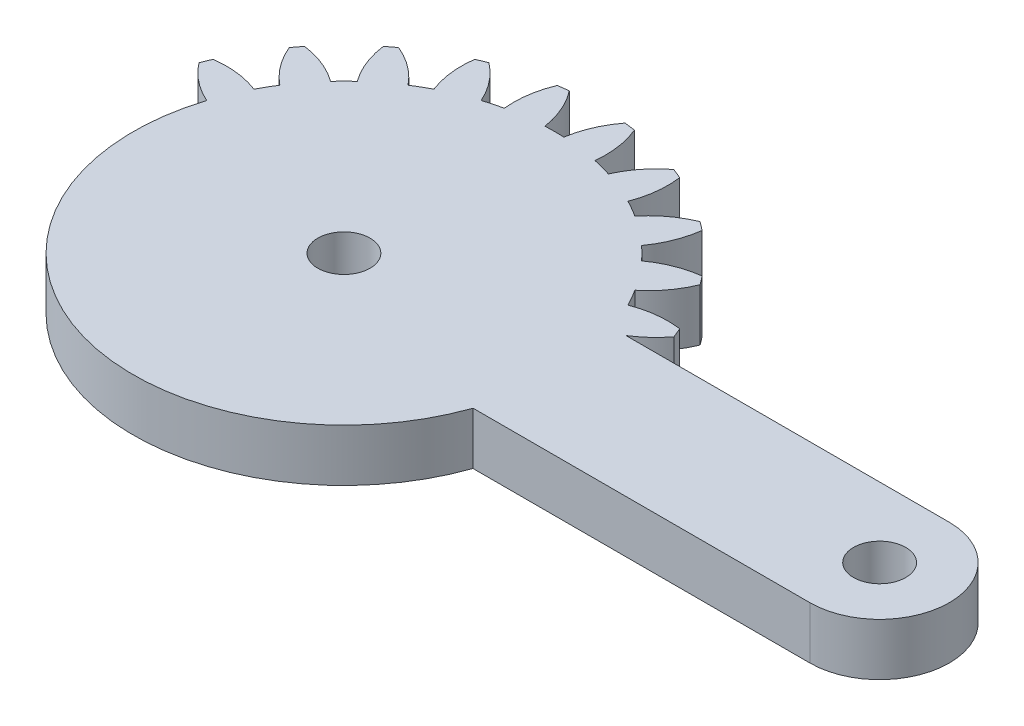
SolidWorks part; units mm, degrees
ref_plane "Front Plane" through (0, 0, 0) normal (0, 0, 1) x (1, 0, 0)
ref_plane "Top Plane" through (0, 0, 0) normal (0, 1, 0) x (1, 0, 0)
ref_plane "Right Plane" through (0, 0, 0) normal (1, 0, 0) x (0, 0, -1)
sketch "Sketch1" plane through (0, 0, 0) normal (0, 1, 0) x (1, 0, 0)
  line L0 (20.6437, 4) -> (2.0816, 4)
  line L1 (2.0816, -4) -> (20.6437, -4)
  arc A0 (2.0816, 4) -> (3.5217, 5.3071) centre (-0.7683, 8.5867) ccw
  arc A1 (3.5217, 5.3071) -> (3.2829, 5.8838) centre (-10.1063, 0) ccw
  arc A2 (3.2829, 5.8838) -> (0.6271, 5.5703) centre (2.5684, 0.5313) ccw
  arc A3 (0.6271, 5.5703) -> (0.0844, 6.5103) centre (-10.1063, 0) ccw
  arc A4 (0.0844, 6.5103) -> (1.6838, 8.6535) centre (-3.3089, 10.711) ccw
  arc A5 (1.6838, 8.6535) -> (1.3038, 9.1487) centre (-10.1063, 0) ccw
  arc A6 (1.3038, 9.1487) -> (-1.1803, 8.1585) centre (1.999, 3.7936) ccw
  arc A7 (-1.1803, 8.1585) -> (-1.9479, 8.926) centre (-10.1063, 0) ccw
  arc A8 (-1.9479, 8.926) -> (-0.9576, 11.4102) centre (-6.3127, 12.1053) ccw
  arc A9 (-0.9576, 11.4102) -> (-1.4528, 11.7901) centre (-10.1063, 0) ccw
  arc A10 (-1.4528, 11.7901) -> (-3.596, 10.1907) centre (0.6046, 6.7975) ccw
  arc A11 (-3.596, 10.1907) -> (-4.5361, 10.7334) centre (-10.1063, 0) ccw
  arc A12 (-4.5361, 10.7334) -> (-4.2225, 13.3892) centre (-9.5751, 12.6747) ccw
  arc A13 (-4.2225, 13.3892) -> (-4.7992, 13.6281) centre (-10.1063, 0) ccw
  arc A14 (-4.7992, 13.6281) -> (-6.4554, 11.5285) centre (-1.5196, 9.3381) ccw
  arc A15 (-6.4554, 11.5285) -> (-7.5039, 11.8094) centre (-10.1063, 0) ccw
  arc A16 (-7.5039, 11.8094) -> (-7.8884, 14.4558) centre (-12.8736, 12.3803) ccw
  arc A17 (-7.8884, 14.4558) -> (-8.5072, 14.5373) centre (-10.1063, 0) ccw
  arc A18 (-8.5072, 14.5373) -> (-9.5636, 12.0806) centre (-4.2291, 11.2423) ccw
  arc A19 (-9.5636, 12.0806) -> (-10.6491, 12.0806) centre (-10.1063, 0) ccw
  arc A20 (-10.6491, 12.0806) -> (-11.7054, 14.5373) centre (-15.9836, 11.2423) ccw
  arc A21 (-11.7054, 14.5373) -> (-12.3243, 14.4558) centre (-10.1063, 0) ccw
  arc A22 (-12.3243, 14.4558) -> (-12.7088, 11.8094) centre (-7.3391, 12.3803) ccw
  arc A23 (-12.7088, 11.8094) -> (-13.7573, 11.5285) centre (-10.1063, 0) ccw
  arc A24 (-13.7573, 11.5285) -> (-15.4135, 13.6281) centre (-18.6931, 9.3381) ccw
  arc A25 (-15.4135, 13.6281) -> (-15.9901, 13.3892) centre (-10.1063, 0) ccw
  arc A26 (-15.9901, 13.3892) -> (-15.6766, 10.7334) centre (-10.6376, 12.6747) ccw
  arc A27 (-15.6766, 10.7334) -> (-16.6166, 10.1907) centre (-10.1063, 0) ccw
  arc A28 (-16.6166, 10.1907) -> (-18.7599, 11.7901) centre (-20.8173, 6.7975) ccw
  arc A29 (-18.7599, 11.7901) -> (-19.255, 11.4102) centre (-10.1063, 0) ccw
  arc A30 (-19.255, 11.4102) -> (-18.2648, 8.926) centre (-13.9, 12.1053) ccw
  arc A31 (-18.2648, 8.926) -> (-19.0324, 8.1585) centre (-10.1063, 0) ccw
  arc A32 (-19.0324, 8.1585) -> (-21.5165, 9.1487) centre (-22.2117, 3.7936) ccw
  arc A33 (-21.5165, 9.1487) -> (-21.8965, 8.6535) centre (-10.1063, 0) ccw
  arc A34 (-21.8965, 8.6535) -> (-20.2971, 6.5103) centre (-16.9038, 10.711) ccw
  arc A35 (-20.2971, 6.5103) -> (-20.8398, 5.5703) centre (-10.1063, 0) ccw
  arc A36 (-20.8398, 5.5703) -> (-23.4956, 5.8838) centre (-22.7811, 0.5313) ccw
  arc A37 (-23.4956, 5.8838) -> (-23.7344, 5.3071) centre (-10.1063, 0) ccw
  arc A38 (-23.7344, 5.3071) -> (-21.6348, 3.6509) centre (-19.4444, 8.5867) ccw
  arc A39 (-21.6348, 3.6509) -> (-21.9157, 2.6025) centre (-10.1063, 0) ccw
  arc A40 (-21.9157, 2.6025) -> (-24.5622, 2.2179) centre (-22.4867, -2.7673) ccw
  arc A41 (-24.5622, 2.2179) -> (-24.6437, 1.5991) centre (-10.1063, 0) ccw
  arc A42 (-24.6437, 1.5991) -> (-22.1869, 0.5427) centre (-21.3486, 5.8773) ccw
  arc A43 (-22.1869, 0.5427) -> (-22.1869, -0.5427) centre (-10.1063, 0) ccw
  arc A44 (-22.1869, -0.5427) -> (-24.6437, -1.5991) centre (-21.3486, -5.8773) ccw
  arc A45 (-24.6437, -1.5991) -> (-24.5622, -2.2179) centre (-10.1063, 0) ccw
  arc A46 (-24.5622, -2.2179) -> (-21.9157, -2.6025) centre (-22.4867, 2.7673) ccw
  arc A47 (-21.9157, -2.6025) -> (-21.6348, -3.6509) centre (-10.1063, 0) ccw
  arc A48 (-21.6348, -3.6509) -> (-23.7344, -5.3071) centre (-19.4444, -8.5867) ccw
  arc A49 (-23.7344, -5.3071) -> (-23.4956, -5.8838) centre (-10.1063, 0) ccw
  arc A50 (-23.4956, -5.8838) -> (-20.8398, -5.5703) centre (-22.7811, -0.5313) ccw
  arc A51 (-20.8398, -5.5703) -> (-20.2971, -6.5103) centre (-10.1063, 0) ccw
  arc A52 (-20.2971, -6.5103) -> (-21.8965, -8.6535) centre (-16.9038, -10.711) ccw
  arc A53 (-21.8965, -8.6535) -> (-21.5165, -9.1487) centre (-10.1063, 0) ccw
  arc A54 (-21.5165, -9.1487) -> (-19.0324, -8.1585) centre (-22.2117, -3.7936) ccw
  arc A55 (-19.0324, -8.1585) -> (-18.2648, -8.926) centre (-10.1063, 0) ccw
  arc A56 (-18.2648, -8.926) -> (-19.255, -11.4102) centre (-13.9, -12.1053) ccw
  arc A57 (-19.255, -11.4102) -> (-18.7599, -11.7901) centre (-10.1063, 0) ccw
  arc A58 (-18.7599, -11.7901) -> (-16.6166, -10.1907) centre (-20.8173, -6.7975) ccw
  arc A59 (-16.6166, -10.1907) -> (-15.6766, -10.7334) centre (-10.1063, 0) ccw
  arc A60 (-15.6766, -10.7334) -> (-15.9901, -13.3892) centre (-10.6376, -12.6747) ccw
  arc A61 (-15.9901, -13.3892) -> (-15.4135, -13.6281) centre (-10.1063, 0) ccw
  arc A62 (-15.4135, -13.6281) -> (-13.7573, -11.5285) centre (-18.6931, -9.3381) ccw
  arc A63 (-13.7573, -11.5285) -> (-12.7088, -11.8094) centre (-10.1063, 0) ccw
  arc A64 (-12.7088, -11.8094) -> (-12.3243, -14.4558) centre (-7.3391, -12.3803) ccw
  arc A65 (-12.3243, -14.4558) -> (-11.7054, -14.5373) centre (-10.1063, 0) ccw
  arc A66 (-11.7054, -14.5373) -> (-10.6491, -12.0806) centre (-15.9836, -11.2423) ccw
  arc A67 (-10.6491, -12.0806) -> (-9.5636, -12.0806) centre (-10.1063, 0) ccw
  arc A68 (-9.5636, -12.0806) -> (-8.5072, -14.5373) centre (-4.2291, -11.2423) ccw
  arc A69 (-8.5072, -14.5373) -> (-7.8884, -14.4558) centre (-10.1063, 0) ccw
  arc A70 (-7.8884, -14.4558) -> (-7.5039, -11.8094) centre (-12.8736, -12.3803) ccw
  arc A71 (-7.5039, -11.8094) -> (-6.4554, -11.5285) centre (-10.1063, 0) ccw
  arc A72 (-6.4554, -11.5285) -> (-4.7992, -13.6281) centre (-1.5196, -9.3381) ccw
  arc A73 (-4.7992, -13.6281) -> (-4.2225, -13.3892) centre (-10.1063, 0) ccw
  arc A74 (-4.2225, -13.3892) -> (-4.5361, -10.7334) centre (-9.5751, -12.6747) ccw
  arc A75 (-4.5361, -10.7334) -> (-3.596, -10.1907) centre (-10.1063, 0) ccw
  arc A76 (-3.596, -10.1907) -> (-1.4528, -11.7901) centre (0.6046, -6.7975) ccw
  arc A77 (-1.4528, -11.7901) -> (-0.9576, -11.4102) centre (-10.1063, 0) ccw
  arc A78 (-0.9576, -11.4102) -> (-1.9479, -8.926) centre (-6.3127, -12.1053) ccw
  arc A79 (-1.9479, -8.926) -> (-1.1803, -8.1585) centre (-10.1063, 0) ccw
  arc A80 (-1.1803, -8.1585) -> (1.3038, -9.1487) centre (1.999, -3.7936) ccw
  arc A81 (1.3038, -9.1487) -> (1.6838, -8.6535) centre (-10.1063, 0) ccw
  arc A82 (1.6838, -8.6535) -> (0.0844, -6.5103) centre (-3.3089, -10.711) ccw
  arc A83 (0.0844, -6.5103) -> (0.6271, -5.5703) centre (-10.1063, 0) ccw
  arc A84 (0.6271, -5.5703) -> (3.2829, -5.8838) centre (2.5684, -0.5313) ccw
  arc A85 (3.2829, -5.8838) -> (3.5217, -5.3071) centre (-10.1063, 0) ccw
  arc A86 (3.5217, -5.3071) -> (2.0816, -4) centre (-0.7683, -8.5867) ccw
  arc A87 (20.6437, -4) -> (20.6437, 4) centre (20.6437, 0) ccw
  circle A88 centre (-10.1063, 0) radius 1.5
  circle A89 centre (20.6437, 0) radius 1.5
  dimension "D1" = 3
  dimension "D2" = 3
extrude "Boss-Extrude1" add sketch "Sketch1" along normal blind 3
sketch "Sketch2" plane through (0, 3, 0) normal (0, 1, 0) x (1, 0, 0)
  line L0 (2.0816, -4) -> (1.3057, -4)
  line L2 (20.6437, 4) -> (2.0816, 4)
  line L3 (2.0816, -4) -> (20.6437, -4)
  line L4 (20.6437, 4) -> (2.0816, 4)
  line L5 (2.0816, -4) -> (20.6437, -4)
  circle A0 centre (-10.1063, 0) radius 12.0927
  arc A88 (20.6437, -4) -> (20.6437, 4) centre (20.6437, 0) ccw
  arc A89 (2.0816, 4) -> (3.5217, 5.3071) centre (-0.7683, 8.5867) ccw
  arc A90 (3.5217, 5.3071) -> (3.2829, 5.8838) centre (-10.1063, 0) ccw
  arc A91 (3.2829, 5.8838) -> (0.6271, 5.5703) centre (2.5684, 0.5313) ccw
  arc A92 (0.6271, 5.5703) -> (0.0844, 6.5103) centre (-10.1063, 0) ccw
  arc A93 (0.0844, 6.5103) -> (1.6838, 8.6535) centre (-3.3089, 10.711) ccw
  arc A94 (1.6838, 8.6535) -> (1.3038, 9.1487) centre (-10.1063, 0) ccw
  arc A95 (1.3038, 9.1487) -> (-1.1803, 8.1585) centre (1.999, 3.7936) ccw
  arc A96 (-1.1803, 8.1585) -> (-1.9479, 8.926) centre (-10.1063, 0) ccw
  arc A97 (-1.9479, 8.926) -> (-0.9576, 11.4102) centre (-6.3127, 12.1053) ccw
  arc A98 (-0.9576, 11.4102) -> (-1.4528, 11.7901) centre (-10.1063, 0) ccw
  arc A99 (-1.4528, 11.7901) -> (-3.596, 10.1907) centre (0.6046, 6.7975) ccw
  arc A100 (-3.596, 10.1907) -> (-4.5361, 10.7334) centre (-10.1063, 0) ccw
  arc A101 (-4.5361, 10.7334) -> (-4.2225, 13.3892) centre (-9.5751, 12.6747) ccw
  arc A102 (-4.2225, 13.3892) -> (-4.7992, 13.6281) centre (-10.1063, 0) ccw
  arc A103 (-4.7992, 13.6281) -> (-6.4554, 11.5285) centre (-1.5196, 9.3381) ccw
  arc A104 (-6.4554, 11.5285) -> (-7.5039, 11.8094) centre (-10.1063, 0) ccw
  arc A105 (-7.5039, 11.8094) -> (-7.8884, 14.4558) centre (-12.8736, 12.3803) ccw
  arc A106 (-7.8884, 14.4558) -> (-8.5072, 14.5373) centre (-10.1063, 0) ccw
  arc A107 (-8.5072, 14.5373) -> (-9.5636, 12.0806) centre (-4.2291, 11.2423) ccw
  arc A108 (-9.5636, 12.0806) -> (-10.6491, 12.0806) centre (-10.1063, 0) ccw
  arc A109 (-10.6491, 12.0806) -> (-11.7054, 14.5373) centre (-15.9836, 11.2423) ccw
  arc A110 (-11.7054, 14.5373) -> (-12.3243, 14.4558) centre (-10.1063, 0) ccw
  arc A111 (-12.3243, 14.4558) -> (-12.7088, 11.8094) centre (-7.3391, 12.3803) ccw
  arc A112 (-12.7088, 11.8094) -> (-13.7573, 11.5285) centre (-10.1063, 0) ccw
  arc A113 (-13.7573, 11.5285) -> (-15.4135, 13.6281) centre (-18.6931, 9.3381) ccw
  arc A114 (-15.4135, 13.6281) -> (-15.9901, 13.3892) centre (-10.1063, 0) ccw
  arc A115 (-15.9901, 13.3892) -> (-15.6766, 10.7334) centre (-10.6376, 12.6747) ccw
  arc A116 (-15.6766, 10.7334) -> (-16.6166, 10.1907) centre (-10.1063, 0) ccw
  arc A117 (-16.6166, 10.1907) -> (-18.7599, 11.7901) centre (-20.8173, 6.7975) ccw
  arc A118 (-18.7599, 11.7901) -> (-19.255, 11.4102) centre (-10.1063, 0) ccw
  arc A119 (-19.255, 11.4102) -> (-18.2648, 8.926) centre (-13.9, 12.1053) ccw
  arc A120 (-18.2648, 8.926) -> (-19.0324, 8.1585) centre (-10.1063, 0) ccw
  arc A121 (-19.0324, 8.1585) -> (-21.5165, 9.1487) centre (-22.2117, 3.7936) ccw
  arc A122 (-21.5165, 9.1487) -> (-21.8965, 8.6535) centre (-10.1063, 0) ccw
  arc A123 (-21.8965, 8.6535) -> (-20.2971, 6.5103) centre (-16.9038, 10.711) ccw
  arc A124 (-20.2971, 6.5103) -> (-20.8398, 5.5703) centre (-10.1063, 0) ccw
  arc A125 (-20.8398, 5.5703) -> (-23.4956, 5.8838) centre (-22.7811, 0.5313) ccw
  arc A126 (-23.4956, 5.8838) -> (-23.7344, 5.3071) centre (-10.1063, 0) ccw
  arc A127 (-23.7344, 5.3071) -> (-21.6348, 3.6509) centre (-19.4444, 8.5867) ccw
  arc A128 (-21.6348, 3.6509) -> (-21.9157, 2.6025) centre (-10.1063, 0) ccw
  arc A129 (-21.9157, 2.6025) -> (-24.5622, 2.2179) centre (-22.4867, -2.7673) ccw
  arc A130 (-24.5622, 2.2179) -> (-24.6437, 1.5991) centre (-10.1063, 0) ccw
  arc A131 (-24.6437, 1.5991) -> (-22.1869, 0.5427) centre (-21.3486, 5.8773) ccw
  arc A132 (-22.1869, 0.5427) -> (-22.1869, -0.5427) centre (-10.1063, 0) ccw
  arc A133 (-22.1869, -0.5427) -> (-24.6437, -1.5991) centre (-21.3486, -5.8773) ccw
  arc A134 (-24.6437, -1.5991) -> (-24.5622, -2.2179) centre (-10.1063, 0) ccw
  arc A135 (-24.5622, -2.2179) -> (-21.9157, -2.6025) centre (-22.4867, 2.7673) ccw
  arc A136 (-21.9157, -2.6025) -> (-21.6348, -3.6509) centre (-10.1063, 0) ccw
  arc A137 (-21.6348, -3.6509) -> (-23.7344, -5.3071) centre (-19.4444, -8.5867) ccw
  arc A138 (-23.7344, -5.3071) -> (-23.4956, -5.8838) centre (-10.1063, 0) ccw
  arc A139 (-23.4956, -5.8838) -> (-20.8398, -5.5703) centre (-22.7811, -0.5313) ccw
  arc A140 (-20.8398, -5.5703) -> (-20.2971, -6.5103) centre (-10.1063, 0) ccw
  arc A141 (-20.2971, -6.5103) -> (-21.8965, -8.6535) centre (-16.9038, -10.711) ccw
  arc A142 (-21.8965, -8.6535) -> (-21.5165, -9.1487) centre (-10.1063, 0) ccw
  arc A143 (-21.5165, -9.1487) -> (-19.0324, -8.1585) centre (-22.2117, -3.7936) ccw
  arc A144 (-19.0324, -8.1585) -> (-18.2648, -8.926) centre (-10.1063, 0) ccw
  arc A145 (-18.2648, -8.926) -> (-19.255, -11.4102) centre (-13.9, -12.1053) ccw
  arc A146 (-19.255, -11.4102) -> (-18.7599, -11.7901) centre (-10.1063, 0) ccw
  arc A147 (-18.7599, -11.7901) -> (-16.6166, -10.1907) centre (-20.8173, -6.7975) ccw
  arc A148 (-16.6166, -10.1907) -> (-15.6766, -10.7334) centre (-10.1063, 0) ccw
  arc A149 (-15.6766, -10.7334) -> (-15.9901, -13.3892) centre (-10.6376, -12.6747) ccw
  arc A150 (-15.9901, -13.3892) -> (-15.4135, -13.6281) centre (-10.1063, 0) ccw
  arc A151 (-15.4135, -13.6281) -> (-13.7573, -11.5285) centre (-18.6931, -9.3381) ccw
  arc A152 (-13.7573, -11.5285) -> (-12.7088, -11.8094) centre (-10.1063, 0) ccw
  arc A153 (-12.7088, -11.8094) -> (-12.3243, -14.4558) centre (-7.3391, -12.3803) ccw
  arc A154 (-12.3243, -14.4558) -> (-11.7054, -14.5373) centre (-10.1063, 0) ccw
  arc A155 (-11.7054, -14.5373) -> (-10.6491, -12.0806) centre (-15.9836, -11.2423) ccw
  arc A156 (-10.6491, -12.0806) -> (-9.5636, -12.0806) centre (-10.1063, 0) ccw
  arc A157 (-9.5636, -12.0806) -> (-8.5072, -14.5373) centre (-4.2291, -11.2423) ccw
  arc A158 (-8.5072, -14.5373) -> (-7.8884, -14.4558) centre (-10.1063, 0) ccw
  arc A159 (-7.8884, -14.4558) -> (-7.5039, -11.8094) centre (-12.8736, -12.3803) ccw
  arc A160 (-7.5039, -11.8094) -> (-6.4554, -11.5285) centre (-10.1063, 0) ccw
  arc A161 (-6.4554, -11.5285) -> (-4.7992, -13.6281) centre (-1.5196, -9.3381) ccw
  arc A162 (-4.7992, -13.6281) -> (-4.2225, -13.3892) centre (-10.1063, 0) ccw
  arc A163 (-4.2225, -13.3892) -> (-4.5361, -10.7334) centre (-9.5751, -12.6747) ccw
  arc A164 (-4.5361, -10.7334) -> (-3.596, -10.1907) centre (-10.1063, 0) ccw
  arc A165 (-3.596, -10.1907) -> (-1.4528, -11.7901) centre (0.6046, -6.7975) ccw
  arc A166 (-1.4528, -11.7901) -> (-0.9576, -11.4102) centre (-10.1063, 0) ccw
  arc A167 (-0.9576, -11.4102) -> (-1.9479, -8.926) centre (-6.3127, -12.1053) ccw
  arc A168 (-1.9479, -8.926) -> (-1.1803, -8.1585) centre (-10.1063, 0) ccw
  arc A169 (-1.1803, -8.1585) -> (1.3038, -9.1487) centre (1.999, -3.7936) ccw
  arc A170 (1.3038, -9.1487) -> (1.6838, -8.6535) centre (-10.1063, 0) ccw
  arc A171 (1.6838, -8.6535) -> (0.0844, -6.5103) centre (-3.3089, -10.711) ccw
  arc A172 (0.0844, -6.5103) -> (0.6271, -5.5703) centre (-10.1063, 0) ccw
  arc A173 (0.6271, -5.5703) -> (3.2829, -5.8838) centre (2.5684, -0.5313) ccw
  arc A174 (3.2829, -5.8838) -> (3.5217, -5.3071) centre (-10.1063, 0) ccw
  arc A175 (3.5217, -5.3071) -> (2.0816, -4) centre (-0.7683, -8.5867) ccw
  arc A176 (20.6437, -4) -> (20.6437, 4) centre (20.6437, 0) ccw
  arc A177 (2.0816, 4) -> (3.5217, 5.3071) centre (-0.7683, 8.5867) ccw
  arc A178 (3.5217, 5.3071) -> (3.2829, 5.8838) centre (-10.1063, 0) ccw
  arc A179 (3.2829, 5.8838) -> (0.6271, 5.5703) centre (2.5684, 0.5313) ccw
  arc A180 (0.6271, 5.5703) -> (0.0844, 6.5103) centre (-10.1063, 0) ccw
  arc A181 (0.0844, 6.5103) -> (1.6838, 8.6535) centre (-3.3089, 10.711) ccw
  arc A182 (1.6838, 8.6535) -> (1.3038, 9.1487) centre (-10.1063, 0) ccw
  arc A183 (1.3038, 9.1487) -> (-1.1803, 8.1585) centre (1.999, 3.7936) ccw
  arc A184 (-1.1803, 8.1585) -> (-1.9479, 8.926) centre (-10.1063, 0) ccw
  arc A185 (-1.9479, 8.926) -> (-0.9576, 11.4102) centre (-6.3127, 12.1053) ccw
  arc A186 (-0.9576, 11.4102) -> (-1.4528, 11.7901) centre (-10.1063, 0) ccw
  arc A187 (-1.4528, 11.7901) -> (-3.596, 10.1907) centre (0.6046, 6.7975) ccw
  arc A188 (-3.596, 10.1907) -> (-4.5361, 10.7334) centre (-10.1063, 0) ccw
  arc A189 (-4.5361, 10.7334) -> (-4.2225, 13.3892) centre (-9.5751, 12.6747) ccw
  arc A190 (-4.2225, 13.3892) -> (-4.7992, 13.6281) centre (-10.1063, 0) ccw
  arc A191 (-4.7992, 13.6281) -> (-6.4554, 11.5285) centre (-1.5196, 9.3381) ccw
  arc A192 (-6.4554, 11.5285) -> (-7.5039, 11.8094) centre (-10.1063, 0) ccw
  arc A193 (-7.5039, 11.8094) -> (-7.8884, 14.4558) centre (-12.8736, 12.3803) ccw
  arc A194 (-7.8884, 14.4558) -> (-8.5072, 14.5373) centre (-10.1063, 0) ccw
  arc A195 (-8.5072, 14.5373) -> (-9.5636, 12.0806) centre (-4.2291, 11.2423) ccw
  arc A196 (-9.5636, 12.0806) -> (-10.6491, 12.0806) centre (-10.1063, 0) ccw
  arc A197 (-10.6491, 12.0806) -> (-11.7054, 14.5373) centre (-15.9836, 11.2423) ccw
  arc A198 (-11.7054, 14.5373) -> (-12.3243, 14.4558) centre (-10.1063, 0) ccw
  arc A199 (-12.3243, 14.4558) -> (-12.7088, 11.8094) centre (-7.3391, 12.3803) ccw
  arc A200 (-12.7088, 11.8094) -> (-13.7573, 11.5285) centre (-10.1063, 0) ccw
  arc A201 (-13.7573, 11.5285) -> (-15.4135, 13.6281) centre (-18.6931, 9.3381) ccw
  arc A202 (-15.4135, 13.6281) -> (-15.9901, 13.3892) centre (-10.1063, 0) ccw
  arc A203 (-15.9901, 13.3892) -> (-15.6766, 10.7334) centre (-10.6376, 12.6747) ccw
  arc A204 (-15.6766, 10.7334) -> (-16.6166, 10.1907) centre (-10.1063, 0) ccw
  arc A205 (-16.6166, 10.1907) -> (-18.7599, 11.7901) centre (-20.8173, 6.7975) ccw
  arc A206 (-18.7599, 11.7901) -> (-19.255, 11.4102) centre (-10.1063, 0) ccw
  arc A207 (-19.255, 11.4102) -> (-18.2648, 8.926) centre (-13.9, 12.1053) ccw
  arc A208 (-18.2648, 8.926) -> (-19.0324, 8.1585) centre (-10.1063, 0) ccw
  arc A209 (-19.0324, 8.1585) -> (-21.5165, 9.1487) centre (-22.2117, 3.7936) ccw
  arc A210 (-21.5165, 9.1487) -> (-21.8965, 8.6535) centre (-10.1063, 0) ccw
  arc A211 (-21.8965, 8.6535) -> (-20.2971, 6.5103) centre (-16.9038, 10.711) ccw
  arc A212 (-20.2971, 6.5103) -> (-20.8398, 5.5703) centre (-10.1063, 0) ccw
  arc A213 (-20.8398, 5.5703) -> (-23.4956, 5.8838) centre (-22.7811, 0.5313) ccw
  arc A214 (-23.4956, 5.8838) -> (-23.7344, 5.3071) centre (-10.1063, 0) ccw
  arc A215 (-23.7344, 5.3071) -> (-21.6348, 3.6509) centre (-19.4444, 8.5867) ccw
  arc A216 (-21.6348, 3.6509) -> (-21.9157, 2.6025) centre (-10.1063, 0) ccw
  arc A217 (-21.9157, 2.6025) -> (-24.5622, 2.2179) centre (-22.4867, -2.7673) ccw
  arc A218 (-24.5622, 2.2179) -> (-24.6437, 1.5991) centre (-10.1063, 0) ccw
  arc A219 (-24.6437, 1.5991) -> (-22.1869, 0.5427) centre (-21.3486, 5.8773) ccw
  arc A220 (-22.1869, 0.5427) -> (-22.1869, -0.5427) centre (-10.1063, 0) ccw
  arc A221 (-22.1869, -0.5427) -> (-24.6437, -1.5991) centre (-21.3486, -5.8773) ccw
  arc A222 (-24.6437, -1.5991) -> (-24.5622, -2.2179) centre (-10.1063, 0) ccw
  arc A223 (-24.5622, -2.2179) -> (-21.9157, -2.6025) centre (-22.4867, 2.7673) ccw
  arc A224 (-21.9157, -2.6025) -> (-21.6348, -3.6509) centre (-10.1063, 0) ccw
  arc A225 (-21.6348, -3.6509) -> (-23.7344, -5.3071) centre (-19.4444, -8.5867) ccw
  arc A226 (-23.7344, -5.3071) -> (-23.4956, -5.8838) centre (-10.1063, 0) ccw
  arc A227 (-23.4956, -5.8838) -> (-20.8398, -5.5703) centre (-22.7811, -0.5313) ccw
  arc A228 (-20.8398, -5.5703) -> (-20.2971, -6.5103) centre (-10.1063, 0) ccw
  arc A229 (-20.2971, -6.5103) -> (-21.8965, -8.6535) centre (-16.9038, -10.711) ccw
  arc A230 (-21.8965, -8.6535) -> (-21.5165, -9.1487) centre (-10.1063, 0) ccw
  arc A231 (-21.5165, -9.1487) -> (-19.0324, -8.1585) centre (-22.2117, -3.7936) ccw
  arc A232 (-19.0324, -8.1585) -> (-18.2648, -8.926) centre (-10.1063, 0) ccw
  arc A233 (-18.2648, -8.926) -> (-19.255, -11.4102) centre (-13.9, -12.1053) ccw
  arc A234 (-19.255, -11.4102) -> (-18.7599, -11.7901) centre (-10.1063, 0) ccw
  arc A235 (-18.7599, -11.7901) -> (-16.6166, -10.1907) centre (-20.8173, -6.7975) ccw
  arc A236 (-16.6166, -10.1907) -> (-15.6766, -10.7334) centre (-10.1063, 0) ccw
  arc A237 (-15.6766, -10.7334) -> (-15.9901, -13.3892) centre (-10.6376, -12.6747) ccw
  arc A238 (-15.9901, -13.3892) -> (-15.4135, -13.6281) centre (-10.1063, 0) ccw
  arc A239 (-15.4135, -13.6281) -> (-13.7573, -11.5285) centre (-18.6931, -9.3381) ccw
  arc A240 (-13.7573, -11.5285) -> (-12.7088, -11.8094) centre (-10.1063, 0) ccw
  arc A241 (-12.7088, -11.8094) -> (-12.3243, -14.4558) centre (-7.3391, -12.3803) ccw
  arc A242 (-12.3243, -14.4558) -> (-11.7054, -14.5373) centre (-10.1063, 0) ccw
  arc A243 (-11.7054, -14.5373) -> (-10.6491, -12.0806) centre (-15.9836, -11.2423) ccw
  arc A244 (-10.6491, -12.0806) -> (-9.5636, -12.0806) centre (-10.1063, 0) ccw
  arc A245 (-9.5636, -12.0806) -> (-8.5072, -14.5373) centre (-4.2291, -11.2423) ccw
  arc A246 (-8.5072, -14.5373) -> (-7.8884, -14.4558) centre (-10.1063, 0) ccw
  arc A247 (-7.8884, -14.4558) -> (-7.5039, -11.8094) centre (-12.8736, -12.3803) ccw
  arc A248 (-7.5039, -11.8094) -> (-6.4554, -11.5285) centre (-10.1063, 0) ccw
  arc A249 (-6.4554, -11.5285) -> (-4.7992, -13.6281) centre (-1.5196, -9.3381) ccw
  arc A250 (-4.7992, -13.6281) -> (-4.2225, -13.3892) centre (-10.1063, 0) ccw
  arc A251 (-4.2225, -13.3892) -> (-4.5361, -10.7334) centre (-9.5751, -12.6747) ccw
  arc A252 (-4.5361, -10.7334) -> (-3.596, -10.1907) centre (-10.1063, 0) ccw
  arc A253 (-3.596, -10.1907) -> (-1.4528, -11.7901) centre (0.6046, -6.7975) ccw
  arc A254 (-1.4528, -11.7901) -> (-0.9576, -11.4102) centre (-10.1063, 0) ccw
  arc A255 (-0.9576, -11.4102) -> (-1.9479, -8.926) centre (-6.3127, -12.1053) ccw
  arc A256 (-1.9479, -8.926) -> (-1.1803, -8.1585) centre (-10.1063, 0) ccw
  arc A257 (-1.1803, -8.1585) -> (1.3038, -9.1487) centre (1.999, -3.7936) ccw
  arc A258 (1.3038, -9.1487) -> (1.6838, -8.6535) centre (-10.1063, 0) ccw
  arc A259 (1.6838, -8.6535) -> (0.0844, -6.5103) centre (-3.3089, -10.711) ccw
  arc A260 (0.0844, -6.5103) -> (0.6271, -5.5703) centre (-10.1063, 0) ccw
  arc A261 (0.6271, -5.5703) -> (3.2829, -5.8838) centre (2.5684, -0.5313) ccw
  arc A262 (3.2829, -5.8838) -> (3.5217, -5.3071) centre (-10.1063, 0) ccw
  arc A263 (3.5217, -5.3071) -> (2.0816, -4) centre (-0.7683, -8.5867) ccw
  dimension "D1" = 0
extrude "Cut-Extrude1" cut sketch "Sketch2" against normal blind 10 contours A222 A223 A0 A221 | A226 A227 A0 A225 | A230 A231 A0 A229 | A234 A235 A0 A233 | A238 A239 A0 A237 | A242 A243 A0 A241 | A246 A247 A0 A245 | A250 A251 A0 A249 | A254 A255 A0 A253 | A258 A259 A0 A257 | A262 A263 L0 A0 A261 | A218 A219 A0 A217
scale "Scale1" bodies to scale 102 scale about centroid uniform scaling yes scale factor 2
